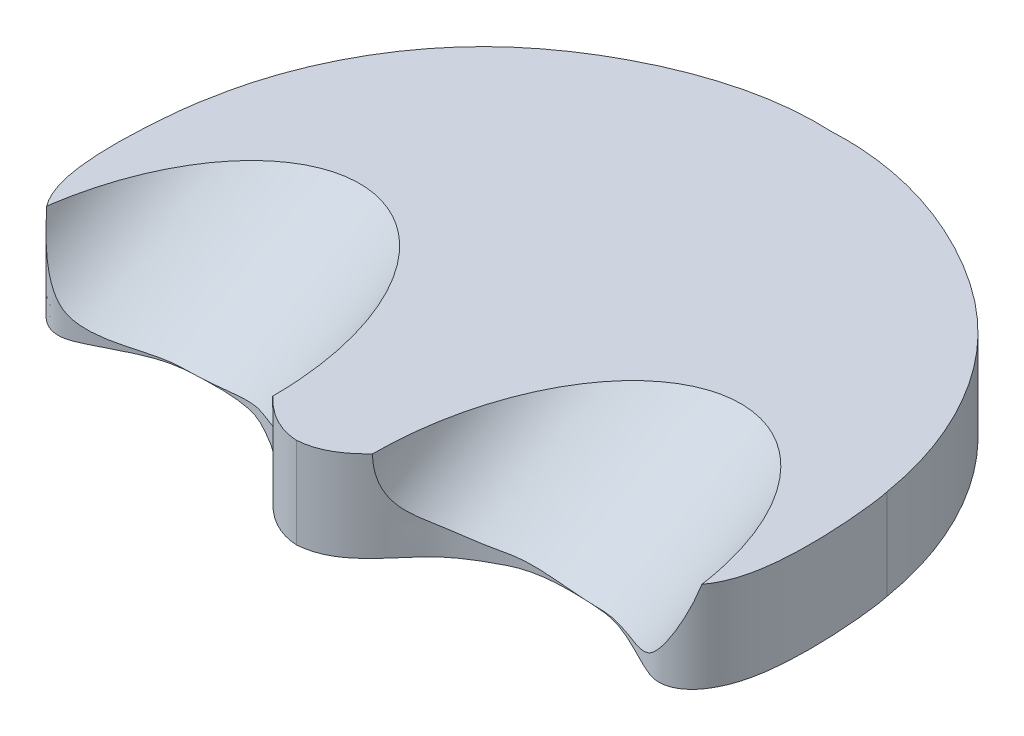
SolidWorks part; units mm, degrees
material "6061-T6 (SS)"
ref_plane "Front Plane" through (0, 0, 0) normal (0, 0, 1) x (1, 0, 0)
ref_plane "Top Plane" through (0, 0, 0) normal (0, 1, 0) x (1, 0, 0)
ref_plane "Right Plane" through (0, 0, 0) normal (1, 0, 0) x (0, 0, -1)
sketch "Sketch3" plane through (0, 0, 0) normal (0, 1, 0) x (1, 0, 0)
  line L0 (0, 0) -> (0, 159.1899) construction
  line L1 (0, 0) -> (0, -140.5301) construction
  line L2 (0, 0) -> (-190.5, 0) construction
  line L3 (0, 0) -> (190.5, 0) construction
  spline S0 degree 3 poles (-190.5, 0) (-184.3927, 37.537) (-157.2613, 93.9641) (-82.3875, 146.6227) (-31.3114, 160.7999) (0, 159.1899) knots 0 0 0 0 0.424401 0.65637 1 1 1 1
  spline S1 degree 3 poles (-190.5, 0) (-192.064, -4.9635) (-201.9672, -83.3146) (-174.6966, -109.29) (-151.6301, -100.568) (-131.4108, -87.7198) (-96.8436, -85.3754) (-78.6925, -86.2588) (-58.8335, -96.8794) (-37.3059, -109.9358) (-21.3496, -139.1148) (0, -140.5301) knots 0 0 0 0 0.166997 0.292321 0.319633 0.426735 0.458914 0.609242 0.64191 0.766802 1 1 1 1
  spline S2 degree 3 poles (190.5, 0) (192.064, -4.9635) (201.9672, -83.3146) (174.6966, -109.29) (151.6301, -100.568) (131.4108, -87.7198) (96.8436, -85.3754) (78.6925, -86.2588) (58.8335, -96.8794) (37.3059, -109.9358) (21.3496, -139.1148) (0, -140.5301) knots 0 0 0 0 0.166997 0.292321 0.319633 0.426735 0.458914 0.609242 0.64191 0.766802 1 1 1 1
  spline S3 degree 3 poles (190.5, 0) (184.3927, 37.537) (157.2613, 93.9641) (82.3875, 146.6227) (31.3114, 160.7999) (0, 159.1899) knots 0 0 0 0 0.424401 0.65637 1 1 1 1
  dimension "D1" = 381
  dimension "D2" = 299.72
  dimension "D3" = 159.1899
  dimension "D4" = 86.8953
  dimension "D5" = 104.4979
  dimension "D6" = 29.1616
  dimension "D7" = 92.2742
  dimension "D8" = 108.411
  dimension "D9" = 67.4883
  dimension "D10" = 43.7314
  dimension "D11" = 117.6915
  dimension "D12" = 162.2568
  dimension "D13" = 89.4522
  dimension "D14" = 140.1036
  dimension "D15" = 175.0666
  dimension "D16" = 50.2669
  dimension "D17" = 101.3666
  dimension "D18" = 138.1225
  dimension "D19" = 155.1557
  dimension "D20" = 192.0074
  dimension "D21" = 193.9268
  dimension "D23" = 76.6666
extrude "Boss-Extrude1" add sketch "Sketch3" along normal blind 50.8 from surface at 0 starting at plane "Top Plane"
sketch "Sketch5" plane through (0, 0, 0) normal (0, -1, 0) x (1, 0, 0)
  line L0 (0, 0) -> (0, -20.32) construction
  line L1 (31.75, -52.07) -> (-31.75, -52.07)
  line L2 (31.75, -52.07) -> (31.75, 11.43)
  line L3 (31.75, 11.43) -> (-31.75, 11.43)
  line L4 (-31.75, -52.07) -> (-31.75, 11.43)
  line L5 (31.75, -52.07) -> (-31.75, 11.43) construction
  line L6 (31.75, 11.43) -> (-31.75, -52.07) construction
  line L7 (-31.75, -52.07) -> (-31.75, -30.48)
  line L8 (-31.75, -30.48) -> (31.75, -30.48) construction
  line L9 (0, -20.32) -> (140.7253, -20.32) construction
  line L10 (0, -20.32) -> (0, -97.1287) construction
  line L11 (0, -20.32) -> (31.9753, -118.7297) construction
  line L13 (0, -20.32) -> (63.8443, -108.1942) construction
  line L14 (0, -20.32) -> (95.5392, -89.7333) construction
  line L15 (124.7166, -60.8429) -> (0, -20.32) construction
  line L16 (0, -20.32) -> (154.5508, 21.0918) construction
  line L17 (0, -20.32) -> (148.922, 65.6601) construction
  line L18 (0, -20.32) -> (-31.9753, -118.7297) construction
  line L19 (0, -20.32) -> (-63.8443, -108.1942) construction
  line L20 (0, -20.32) -> (-95.5392, -89.7333) construction
  line L21 (-124.7166, -60.8429) -> (0, -20.32) construction
  line L22 (0, -20.32) -> (-154.5508, 21.0918) construction
  line L23 (0, -20.32) -> (-148.922, 65.6601) construction
  spline S0 degree 3 poles (-148.922, 65.6601) (-157.8584, 40.2253) (-156.2837, 8.5854) (-143.1202, -28.9506) (-139.3242, -37.3463) (-130.3709, -53.1962) (-125.215, -60.649) (-118.0488, -69.1403) (-116.5795, -70.7975) (-113.5719, -74.0252) (-112.0368, -75.592) (-107.2801, -80.2116) (-103.9215, -83.1695) (-93.3361, -91.6595) (-85.5959, -96.8074) (-76.3408, -101.9556) (-75.3049, -102.5187) (-73.219, -103.6268) (-72.1677, -104.1726) (-69.0049, -105.7765) (-66.8862, -106.8006) (-60.5068, -109.7299) (-56.2231, -111.4921) (-47.6308, -114.6027) (-43.3223, -115.9511) (-34.7104, -118.209) (-30.4072, -119.1185) (-21.8242, -120.4791) (-17.5446, -120.9304) (-11.1443, -121.2499) (-9.0138, -121.2968) (-5.8216, -121.2757) (-4.1848, -121.2414) (-2.5489, -121.1705) (-1.9677, -121.1408) (-1.9605, -121.1404) (-1.2995, -121.1064) (-0.6497, -121.073) (0, -121.0396) knots -0.292878 -0.292878 -0.292878 -0.292878 0.125 0.125 0.25 0.25 0.375 0.375 0.40625 0.40625 0.4375 0.4375 0.5 0.5 0.625 0.625 0.640625 0.640625 0.65625 0.65625 0.6875 0.6875 0.75 0.75 0.8125 0.8125 0.875 0.875 0.9375 0.9375 0.96875 0.96875 0.984375 0.992798 0.992798 0.99292 0.99292 1 1 1 1
  spline S5 degree 3 poles (998.6789, -69.6893) (665.1581, -86.8384) (331.6156, -103.9885) (-1.9268, -121.1387) (-1.9605, -121.1404) (-1.9677, -121.1408) (-2.5489, -121.1705) (-4.1848, -121.2414) (-5.8216, -121.2757) (-9.0138, -121.2968) (-11.1443, -121.2499) (-17.5446, -120.9304) (-21.8242, -120.4791) (-30.4072, -119.1185) (-34.7104, -118.209) (-43.3223, -115.9511) (-47.6308, -114.6027) (-56.2231, -111.4921) (-60.5068, -109.7299) (-66.8862, -106.8006) (-69.0049, -105.7765) (-72.1677, -104.1726) (-73.219, -103.6268) (-75.3049, -102.5187) (-76.3408, -101.9556) (-85.5959, -96.8074) (-93.3361, -91.6595) (-103.9215, -83.1695) (-107.2801, -80.2116) (-112.0368, -75.592) (-113.5719, -74.0252) (-116.5795, -70.7975) (-118.0488, -69.1403) (-125.215, -60.649) (-130.3709, -53.1962) (-139.3242, -37.3463) (-143.1202, -28.9506) (-198.5095, 128.9933) (-22.362, 351.6373) (651.8169, -587.5188) knots -3.627409 -3.627409 -3.627409 -3.627409 0.006836 0.00708 0.00708 0.007202 0.007202 0.015625 0.03125 0.03125 0.0625 0.0625 0.125 0.125 0.1875 0.1875 0.25 0.25 0.3125 0.3125 0.34375 0.34375 0.359375 0.359375 0.375 0.375 0.5 0.5 0.5625 0.5625 0.59375 0.59375 0.625 0.625 0.75 0.75 0.875 0.875 3.034324 3.034324 3.034324 3.034324 only from (0, -121.0396) to (-152.8945, 6.1184)
  spline S6 degree 3 poles (-1687.8289, -2297.0686) (-150.4269, 537.0593) (218.9922, 187.4002) (143.1202, -28.9506) (139.3242, -37.3463) (130.3709, -53.1962) (125.215, -60.649) (118.0488, -69.1403) (116.5795, -70.7975) (113.5719, -74.0252) (112.0368, -75.592) (107.2801, -80.2116) (103.9215, -83.1695) (93.3361, -91.6595) (85.5959, -96.8074) (76.3408, -101.9556) (75.3049, -102.5187) (73.219, -103.6268) (72.1677, -104.1726) (69.0049, -105.7765) (66.8862, -106.8006) (60.5068, -109.7299) (56.2231, -111.4921) (47.6308, -114.6027) (43.3223, -115.9511) (34.7104, -118.209) (30.4072, -119.1185) (21.8242, -120.4791) (17.5446, -120.9304) (11.1443, -121.2499) (9.0138, -121.2968) (5.8216, -121.2757) (4.1848, -121.2414) (2.5489, -121.1705) (1.9677, -121.1408) (1.9605, -121.1404) (-997.3522, -69.7575) (-1996.6535, -18.3753) (-2996.029, 33.0152) knots -2.879056 -2.879056 -2.879056 -2.879056 0.125 0.125 0.25 0.25 0.375 0.375 0.40625 0.40625 0.4375 0.4375 0.5 0.5 0.625 0.625 0.640625 0.640625 0.65625 0.65625 0.6875 0.6875 0.75 0.75 0.8125 0.8125 0.875 0.875 0.9375 0.9375 0.96875 0.96875 0.984375 0.992798 0.992798 0.99292 0.99292 11.881939 11.881939 11.881939 11.881939 only from (152.8945, 6.1184) to (0, -121.0396)
  spline S8 degree 3 poles (148.922, 65.6601) (157.8584, 40.2253) (156.2837, 8.5854) (143.1202, -28.9506) (139.3242, -37.3463) (130.3709, -53.1962) (125.215, -60.649) (118.0488, -69.1403) (116.5795, -70.7975) (113.5719, -74.0252) (112.0368, -75.592) (107.2801, -80.2116) (103.9215, -83.1695) (93.3361, -91.6595) (85.5959, -96.8074) (76.3408, -101.9556) (75.3049, -102.5187) (73.219, -103.6268) (72.1677, -104.1726) (69.0049, -105.7765) (66.8862, -106.8006) (60.5068, -109.7299) (56.2231, -111.4921) (47.6308, -114.6027) (43.3223, -115.9511) (34.7104, -118.209) (30.4072, -119.1185) (21.8242, -120.4791) (17.5446, -120.9304) (11.1443, -121.2499) (9.0138, -121.2968) (5.8216, -121.2757) (4.1848, -121.2414) (2.5489, -121.1705) (1.9677, -121.1408) (1.9605, -121.1404) (1.2995, -121.1064) (0.6497, -121.073) (0, -121.0396) knots -0.292878 -0.292878 -0.292878 -0.292878 0.125 0.125 0.25 0.25 0.375 0.375 0.40625 0.40625 0.4375 0.4375 0.5 0.5 0.625 0.625 0.640625 0.640625 0.65625 0.65625 0.6875 0.6875 0.75 0.75 0.8125 0.8125 0.875 0.875 0.9375 0.9375 0.96875 0.96875 0.984375 0.992798 0.992798 0.99292 0.99292 1 1 1 1
  point P0 (0, -20.32)
  point P3 (0, -20.32)
  point P14 (0, 114.3)
  point P16 (0, 88.9)
  dimension "D1" = 20.32
  dimension "D2" = 63.5
  dimension "D3" = 63.5
  dimension "D4" = 21.59
  dimension "D6" = 25.4
  dimension "D7" = 88.9
  dimension "D8" = 18
  dimension "D9" = 18
  dimension "D10" = 18
  dimension "D11" = 18
  dimension "D12" = 15
  dimension "D13" = 15
  dimension "D5" = 38.1
sketch "Sketch7" plane through (0, 50.8, 0) normal (0, 1, 0) x (1, 0, 0)
  line L0 (-193.6723, -25.4) -> (193.6723, -25.4) construction
  spline S0 degree 3 poles (-190.5, 0) (-192.064, -4.9635) (-201.9672, -83.3146) (-174.6966, -109.29) (-151.6301, -100.568) (-131.4108, -87.7198) (-96.8436, -85.3754) (-78.6925, -86.2588) (-58.8335, -96.8794) (-37.3059, -109.9358) (-21.3496, -139.1148) (0, -140.5301) knots 0 0 0 0 0.166997 0.292321 0.319633 0.426735 0.458914 0.609242 0.64191 0.766802 1 1 1 1 construction
  spline S1 degree 3 poles (0, -140.5301) (21.3496, -139.1148) (37.3059, -109.9358) (58.8335, -96.8794) (78.6925, -86.2588) (96.8436, -85.3754) (131.4108, -87.7198) (151.6301, -100.568) (174.6966, -109.29) (201.9672, -83.3146) (192.064, -4.9635) (190.5, 0) knots 0 0 0 0 0.233198 0.35809 0.390758 0.541086 0.573265 0.680367 0.707679 0.833003 1 1 1 1 construction
  point P6 (0, 0)
  dimension "D1" = 25.4
ref_plane "Plane2" through (0, 1.7015, -2.947) normal (0, -0.5, 0.866) x (1, 0, 0)
sketch "Sketch6" plane through (0, 24.0865, 9.977) normal (0, 0.5, -0.866) x (-1, 0, 0)
  line L2 (0, 2.092) -> (0, -53.788) construction
  ellipse E0 centre (-106.8082, 81.0265) end of major axis (-185.6422, 81.0265) minor radius 63.7725
  ellipse E1 centre (106.8082, 81.0265) end of major axis (27.9741, 81.0265) minor radius 63.7725
  spline S3 degree 3 poles (0, 44.417) (-21.3496, 43.7094) (-37.3059, 29.1199) (-58.8335, 22.5917) (-78.6925, 17.2814) (-96.8436, 16.8397) (-131.4108, 18.0119) (-151.6301, 24.436) (-174.6966, 28.797) (-201.9672, 15.8093) (-192.064, -23.3663) (-190.5, -25.848) knots 0 0 0 0 0.233198 0.35809 0.390758 0.541086 0.573265 0.680367 0.707679 0.833003 1 1 1 1 construction
  spline S5 degree 3 poles (0, 88.4111) (-21.3496, 87.7035) (-37.3059, 73.114) (-58.8335, 66.5858) (-78.6925, 61.2755) (-96.8436, 60.8338) (-131.4108, 62.006) (-151.6301, 68.4301) (-174.6966, 72.7911) (-201.9672, 59.8034) (-192.064, 20.6278) (-190.5, 18.1461) knots 0 0 0 0 0.233198 0.35809 0.390758 0.541086 0.573265 0.680367 0.707679 0.833003 1 1 1 1 construction
  point P52 (0, -25.848)
  dimension "D1" = 106.8745
  dimension "D2" = 106.8082
extrude "Cut-Extrude1" cut sketch "Sketch6" against normal through all and the other way through all
equation "\"Plate thickness\"=2"
equation "\"D1@Boss-Extrude1\"=\"Plate thickness\""
equation "\"Bracket Alignment\"= .80"
equation "\"D1@Sketch5\"=\"Bracket Alignment\""
